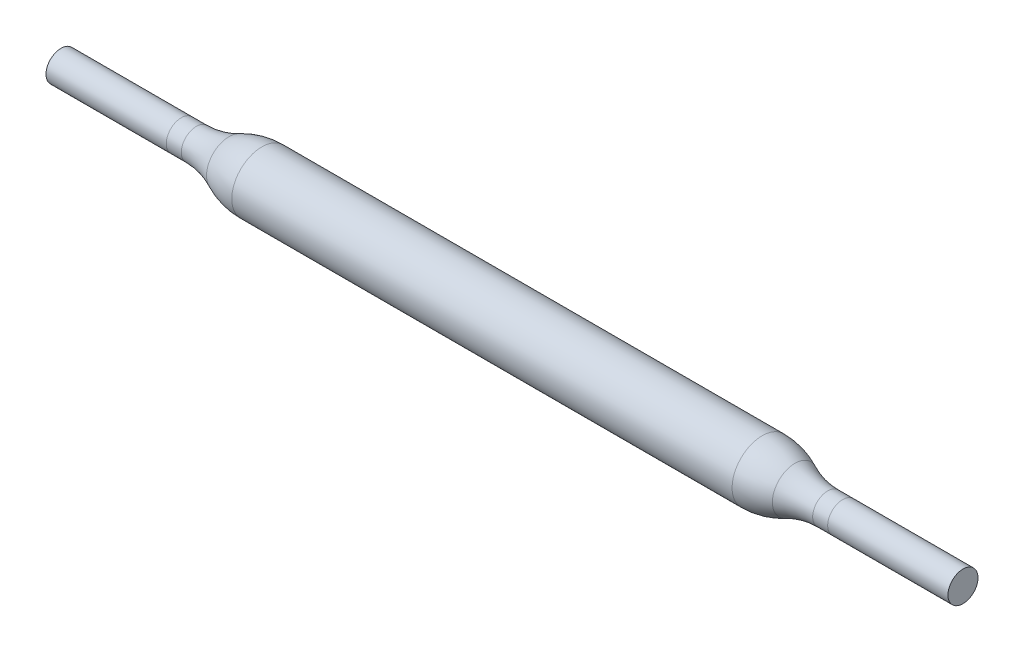
SolidWorks part; units mm, degrees
ref_plane "Front Plane" through (0, 0, 0) normal (0, 0, 1) x (1, 0, 0)
ref_plane "Top Plane" through (0, 0, 0) normal (0, 1, 0) x (1, 0, 0)
ref_plane "Right Plane" through (0, 0, 0) normal (1, 0, 0) x (0, 0, -1)
sketch "Sketch1" plane through (0, 0, 0) normal (0, 0, 1) x (1, 0, 0)
  line L0 (-30, 0) -> (30, 0)
  line L1 (30, 0) -> (30, 1)
  line L2 (-30, 0) -> (-30, 1)
  line L3 (-30, 1) -> (-21, 1)
  line L4 (30, 1) -> (21, 1)
  line L5 (-16.6411, 2) -> (16.6411, 2)
  arc A0 (-21, 1) -> (-18.8206, 1.5) centre (-21, 6) ccw
  arc A1 (21, 1) -> (18.8206, 1.5) centre (21, 6) cw
  arc A2 (16.6411, 2) -> (18.8206, 1.5) centre (16.6411, -3) cw
  arc A3 (-16.6411, 2) -> (-18.8206, 1.5) centre (-16.6411, -3) ccw
  point P2 (0, 0)
  point P10 (0, 2)
  point P18 (-18, 2)
  dimension "D7" = 5
  dimension "D1" = 60
  dimension "D2" = 1
  dimension "D3" = 9
  dimension "D4" = 9
  dimension "D5" = 2
  dimension "D6" = 3
revolve "Revolve1" add sketch "Sketch1" angle 360 about L0
sketch "Sketch2" plane through (0, 0, 0) normal (0, 0, 1) x (1, 0, 0)
  line L0 (-22, 4.4747) -> (-22, -5.414)
  line L1 (22, 4.4747) -> (22, -4.5092)
  line L2 (-30, 1) -> (-30, -1) construction
  line L3 (30, -1) -> (30, 1) construction
  dimension "D1" = 8
  dimension "D2" = 8
split line "Split Line1"
scale "Scale1" scale about centroid uniform scaling yes scale factor 18
